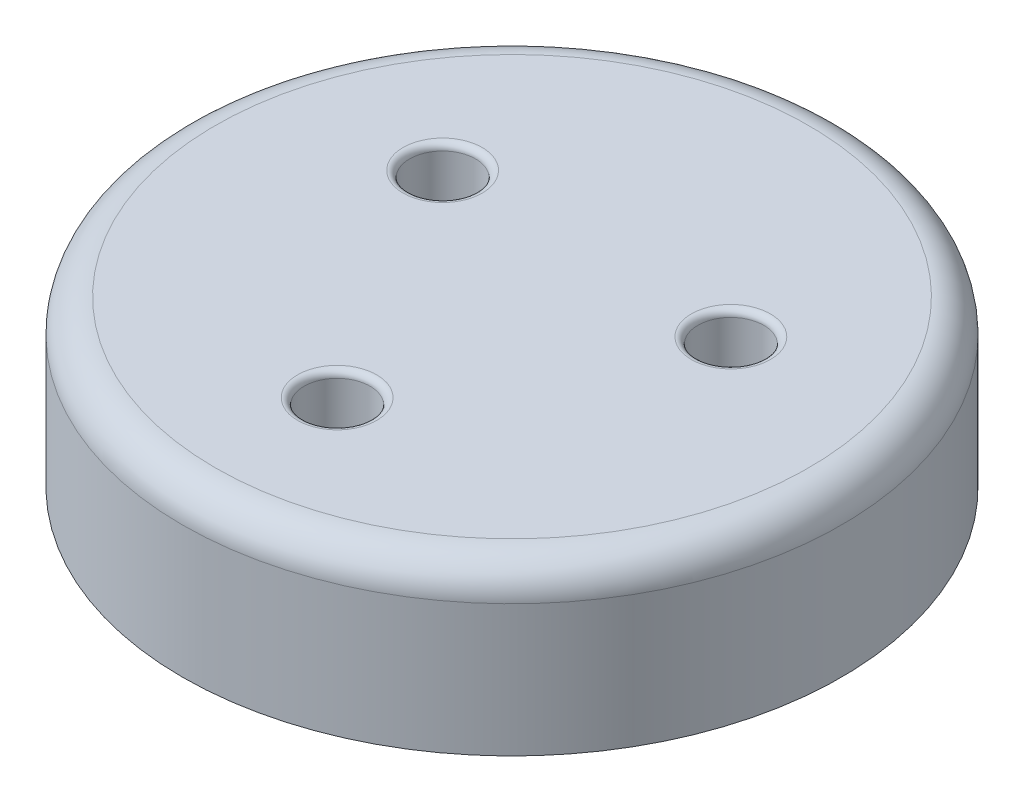
SolidWorks part; units mm, degrees
ref_plane "Front Plane" through (0, 0, 0) normal (0, 0, 1) x (1, 0, 0)
ref_plane "Top Plane" through (0, 0, 0) normal (0, 1, 0) x (1, 0, 0)
ref_plane "Right Plane" through (0, 0, 0) normal (1, 0, 0) x (0, 0, -1)
sketch "Sketch1" plane through (0, 0, 0) normal (0, 1, 0) x (1, 0, 0)
  line L0 (0, 0) -> (-4.3729, 2.2682) construction
  line L1 (-4.3729, 2.2682) -> (4.3729, 2.2682) construction
  line L2 (4.3729, 2.2682) -> (0, 0) construction
  line L3 (0, 0) -> (0, -5.3059) construction
  line L4 (0, -5.3059) -> (-4.3729, 2.2682) construction
  line L5 (4.3729, 2.2682) -> (0, -5.3059) construction
  circle A0 centre (0, 0) radius 10
  circle A1 centre (-4.3729, 2.2682) radius 1
  circle A2 centre (4.3729, 2.2682) radius 1
  circle A3 centre (0, -5.3059) radius 1
  dimension "D1" = 20
  dimension "D2" = 2
extrude "Boss-Extrude1" add sketch "Sketch1" along normal blind 5
fillet "Fillet1" radius 1 1 edges at (0, 5, 10)
fillet "Fillet2" radius 0.2 3 edges at (0, 5, 6.3059) (4.3729, 5, -1.2682) (-4.3729, 5, -1.2682)
sketch "Sketch4" plane through (0, 0, 0) normal (0, -1, 0) x (1, 0, 0)
  line L0 (0, 0) -> (0, -10) construction
  circle A0 centre (0, 0) radius 10 construction
